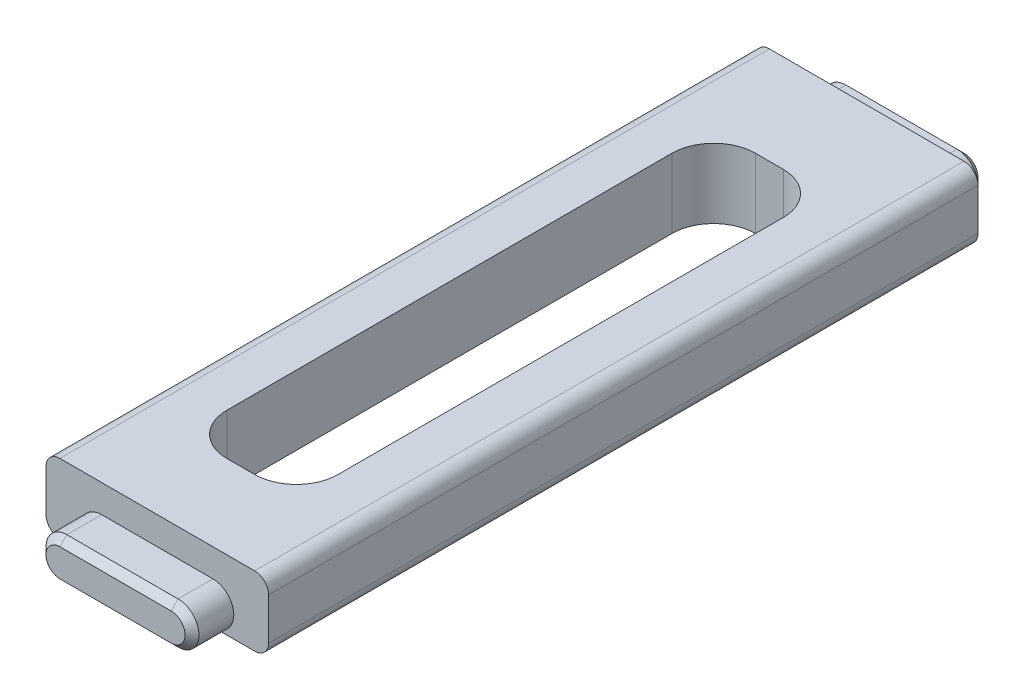
SolidWorks part; units mm, degrees
material "PLA"
ref_plane "前视基准面" through (0, 0, 0) normal (0, 0, 1) x (1, 0, 0)
ref_plane "上视基准面" through (0, 0, 0) normal (0, 1, 0) x (1, 0, 0)
ref_plane "右视基准面" through (0, 0, 0) normal (1, 0, 0) x (0, 0, -1)
sketch "草图1" plane through (0, 0, 0) normal (0, 0, 1) x (1, 0, 0)
  line L0 (-4, 0) -> (4, 0) construction
  line L1 (-4, 1.5) -> (4, 1.5)
  line L2 (-4, -1.5) -> (4, -1.5)
  arc A0 (-4, 1.5) -> (-4, -1.5) centre (-4, 0) ccw
  arc A1 (4, -1.5) -> (4, 1.5) centre (4, 0) ccw
  point P3 (0, 0)
  dimension "D2" = 1.5
  dimension "D1" = 8
extrude "凸台-拉伸1" add sketch "草图1" along normal blind 3
sketch "草图2" plane through (0, 0, 0) normal (0, 0, -1) x (-1, 0, 0)
  line L0 (8, -1.5) -> (-8, -1.5)
  line L2 (-8, -1.5) -> (-8, 3.5)
  line L3 (-8, 3.5) -> (8, 3.5)
  line L4 (8, 3.5) -> (8, -1.5)
  line L5 (4, -1.5) -> (-4, -1.5) construction
  point P3 (0, -1.5)
  dimension "D1" = 5
  dimension "D2" = 16
extrude "凸台-拉伸2" add sketch "草图2" along normal blind 51
sketch "草图3" plane through (0, 0, -51) normal (0, 0, -1) x (-1, 0, 0)
  line L0 (-4, 0) -> (4, 0) construction
  line L2 (-4, 1.5) -> (4, 1.5)
  line L3 (-4, -1.5) -> (4, -1.5)
  arc A0 (-4, 1.5) -> (-4, -1.5) centre (-4, 0) ccw
  arc A1 (4, -1.5) -> (4, 1.5) centre (4, 0) ccw
  point P5 (0, 0)
  dimension "D2" = 1.5
  dimension "D1" = 8
extrude "凸台-拉伸3" add sketch "草图3" along normal blind 3
fillet "圆角1" radius 1 4 edges at (8, -1.5, -25.5) (-8, -1.5, -25.5) (8, 3.5, -25.5) (-8, 3.5, -25.5)
chamfer "倒角1" distance 0.5 angle 45 8 edges at (0, 1.5, 3) (5.5, 0, 3) (0, -1.5, 3) (-5.5, 0, 3) (0, 1.5, -54) (-5.5, 0, -54) (0, -1.5, -54) (5.5, 0, -54)
sketch "草图4" plane through (0, -1.5, 0) normal (0, -1, 0) x (1, 0, 0)
  line L0 (-4, 3) -> (4, 3) construction
  line L1 (-4, -44) -> (4, -44)
  line L2 (-4, -44) -> (-4, -6)
  line L3 (-4, -6) -> (4, -6)
  line L4 (4, -44) -> (4, -6)
  line L5 (-4, -44) -> (4, -6) construction
  line L6 (-4, -6) -> (4, -44) construction
  point P0 (0, -25)
  dimension "D1" = 38
  dimension "D2" = 8
  dimension "D3" = 28
extrude "切除-拉伸1" cut sketch "草图4" against normal through all
fillet "圆角2" radius 3 4 edges at (-4, 1, -44) (4, 1, -44) (-4, 1, -6) (4, 1, -6)
